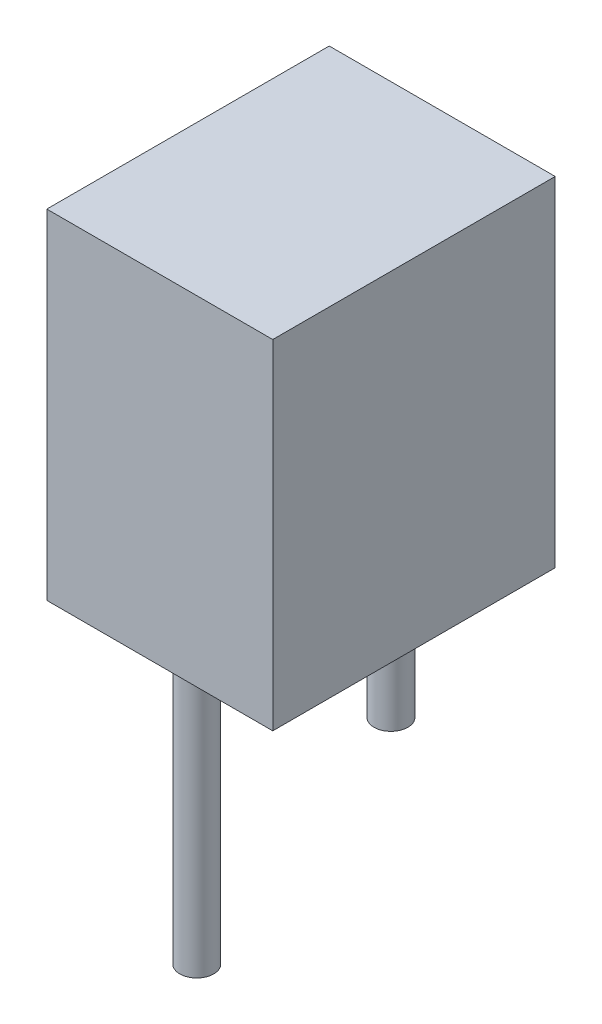
SolidWorks part; units mm, degrees
ref_plane "Front Plane" through (0, 0, 0) normal (0, 0, 1) x (1, 0, 0)
ref_plane "Top Plane" through (0, 0, 0) normal (0, 1, 0) x (1, 0, 0)
ref_plane "Right Plane" through (0, 0, 0) normal (1, 0, 0) x (0, 0, -1)
sketch "Sketch1" plane through (0, 0, 0) normal (0, 0, 1) x (1, 0, 0)
  line L1 (10, -15) -> (-10, -15)
  line L2 (10, -15) -> (10, 15)
  line L3 (10, 15) -> (-10, 15)
  line L4 (-10, -15) -> (-10, 15)
  line L5 (10, -15) -> (-10, 15) construction
  line L6 (10, 15) -> (-10, -15) construction
  point P0 (0, 0)
  dimension "D1" = 20
  dimension "D2" = 30
extrude "Boss-Extrude1" add sketch "Sketch1" along normal mid plane 25
sketch "Sketch2" plane through (0, -15, 0) normal (0, -1, 0) x (1, 0, 0)
  circle A0 centre (-5.476, 3.75) radius 1.5
  circle A1 centre (5.2113, -2.75) radius 1.5
  dimension "D3" = 3
  dimension "D4" = 3
  dimension "D1" = 3.75
  dimension "D2" = 2.75
extrude "Boss-Extrude2" add sketch "Sketch2" along normal blind 30
sketch "Sketch3" plane through (0, -45, 0) normal (0, -1, 0) x (1, 0, 0)
  circle A0 centre (5.2113, -2.75) radius 1.5
extrude "Cut-Extrude1" cut sketch "Sketch3" against normal blind 21
sketch "Sketch4" plane through (0, 0, -12.5) normal (0, 0, -1) x (-1, 0, 0)
  line L0 (-5.7572, 2.1663) -> (6.0749, 2.1663) construction
  line L1 (-5.7572, -1.3415) -> (6.0749, -1.3415) construction
  line L2 (-5.7572, -4.5257) -> (6.0749, -4.5257) construction
  text T0 "BLOOD" font "Century Gothic" height in points 10
  text T1 "ANALYSE" font "Century Gothic" height in points 8
  text T2 "BLOCK" font "Century Gothic" height in points 9
extrude "Cut-Extrude2" cut sketch "Sketch4" against normal blind 1
